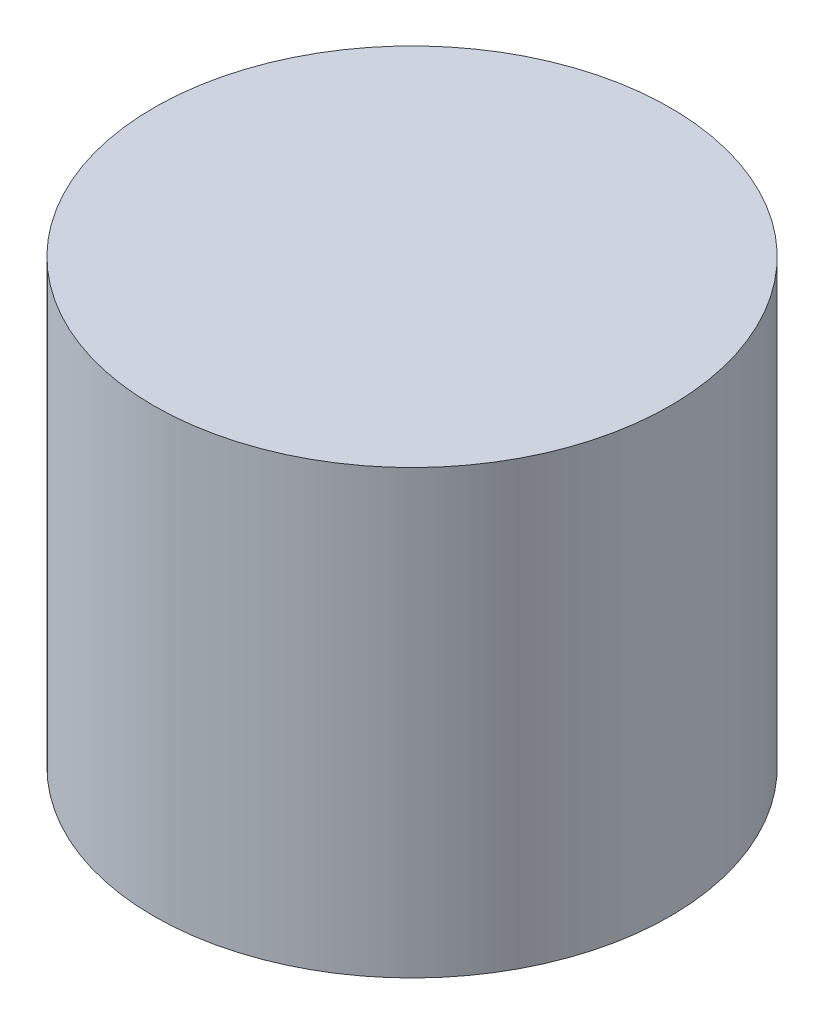
SolidWorks part; units mm, degrees
ref_plane "Front Plane" through (0, 0, 0) normal (0, 0, 1) x (1, 0, 0)
ref_plane "Top Plane" through (0, 0, 0) normal (0, 1, 0) x (1, 0, 0)
ref_plane "Right Plane" through (0, 0, 0) normal (1, 0, 0) x (0, 0, -1)
sketch "Sketch1" plane through (0, 0, 0) normal (0, 1, 0) x (1, 0, 0)
  circle A0 centre (0, 0) radius 12.5
  dimension "D1" = 25
extrude "Boss-Extrude1" add sketch "Sketch1" along normal blind 21.4
